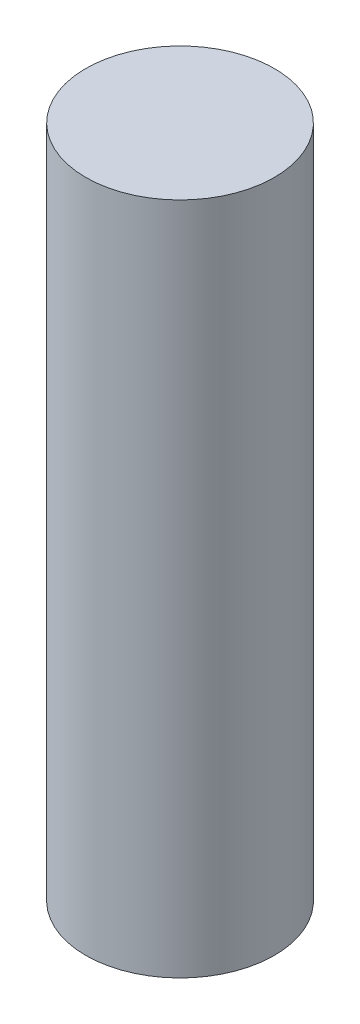
SolidWorks part; units mm, degrees
ref_plane "정면" through (0, 0, 0) normal (0, 0, 1) x (1, 0, 0)
ref_plane "윗면" through (0, 0, 0) normal (0, 1, 0) x (1, 0, 0)
ref_plane "우측면" through (0, 0, 0) normal (1, 0, 0) x (0, 0, -1)
sketch "Sketch1" plane through (0, 0, 0) normal (0, 1, 0) x (1, 0, 0)
  circle A0 centre (0, 0) radius 3.5
  dimension "D1" = 7
extrude "Boss-Extrude1" add sketch "Sketch1" along normal blind 25
